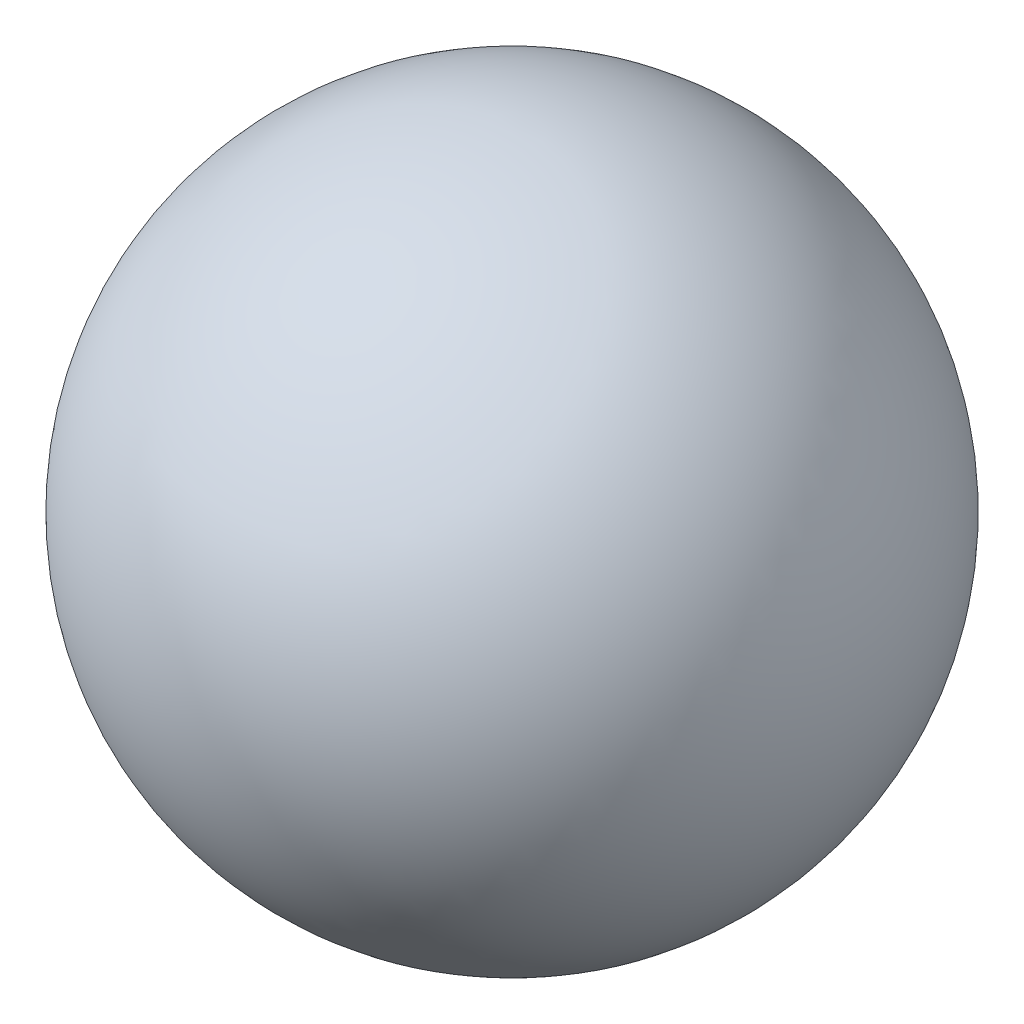
SolidWorks part; units mm, degrees
ref_plane "Front Plane" through (0, 0, 0) normal (0, 0, 1) x (1, 0, 0)
ref_plane "Top Plane" through (0, 0, 0) normal (0, 1, 0) x (1, 0, 0)
ref_plane "Right Plane" through (0, 0, 0) normal (1, 0, 0) x (0, 0, -1)
sketch "Sketch2" plane through (0, 0, 0) normal (0, 0, 1) x (1, 0, 0)
  line L0 (0, 19.6873) -> (0, -19.6873)
  arc A0 (0, -19.6873) -> (0, 19.6873) centre (0, 0) ccw
  dimension "D1" = 39.3747
revolve "Revolve2" add sketch "Sketch2" angle 360 about L0
